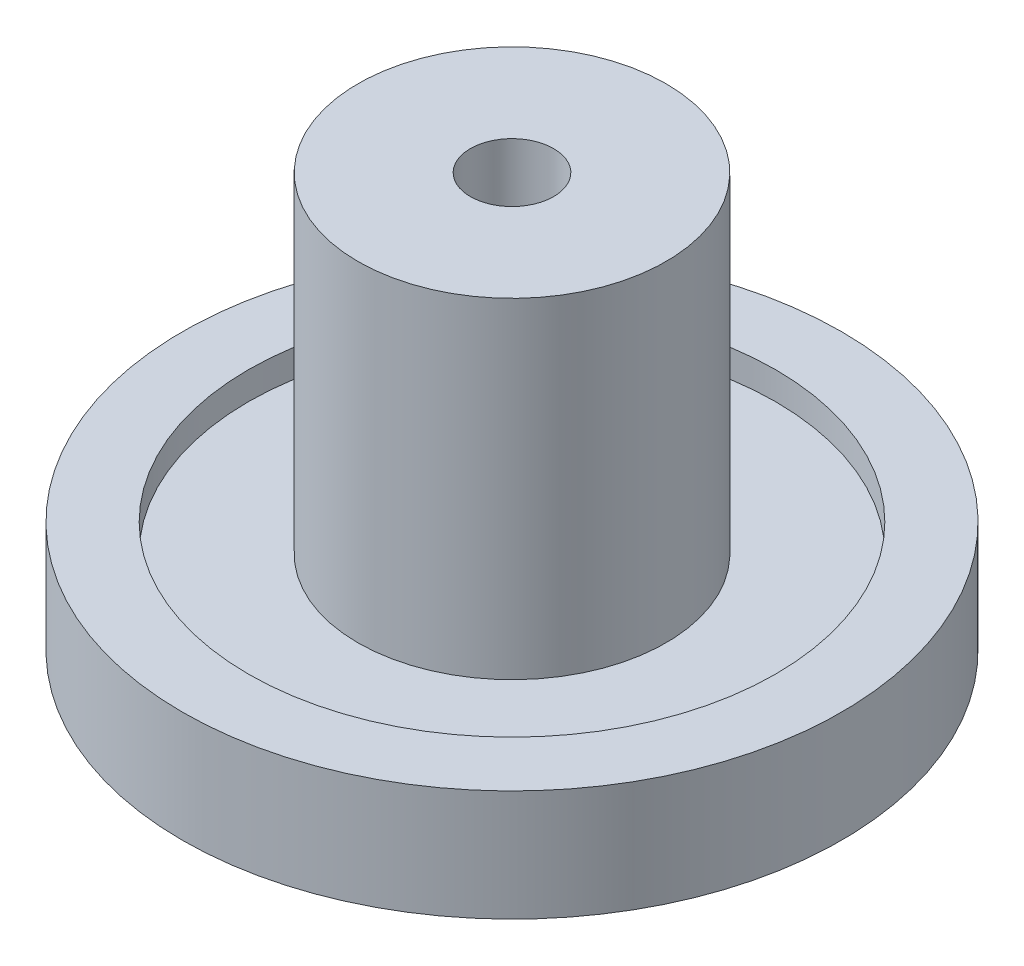
SolidWorks part; units mm, degrees
material "Nylon 101"
ref_plane "Front Plane" through (0, 0, 0) normal (0, 0, 1) x (1, 0, 0)
ref_plane "Top Plane" through (0, 0, 0) normal (0, 1, 0) x (1, 0, 0)
ref_plane "Right Plane" through (0, 0, 0) normal (1, 0, 0) x (0, 0, -1)
sketch "Sketch1" plane through (0, 0, 0) normal (0, 0, 1) x (1, 0, 0)
  line L0 (0, 0) -> (0, 14.9) construction
  line L1 (1.5, 14.9) -> (1.5, 0)
  line L2 (1.5, 0) -> (3.5, 0)
  line L3 (3.5, 0) -> (3.5, 1.2)
  line L4 (3.5, 1.2) -> (9.5, 1.2)
  line L5 (9.5, 1.2) -> (9.5, 0)
  line L6 (9.5, 0) -> (11.875, 0)
  line L7 (11.875, 0) -> (11.875, 4)
  line L8 (11.875, 4) -> (9.5, 4)
  line L9 (9.5, 4) -> (9.5, 3)
  line L10 (9.5, 3) -> (5.55, 3)
  line L11 (5.55, 3) -> (5.55, 14.9)
  line L12 (5.55, 14.9) -> (1.5, 14.9)
  line L13 (0, 14.9) -> (1.5, 14.9) construction
  line L14 (0, 0) -> (1.5, 0) construction
  dimension "D1" = 3
  dimension "D2" = 7
  dimension "D3" = 19
  dimension "D4" = 23.75
  dimension "D5" = 11.1
  dimension "D6" = 1.2
  dimension "D7" = 1
  dimension "D8" = 4
  dimension "D9" = 14.9
revolve "20 and 58" add sketch "Sketch1" angle 360 about L0
